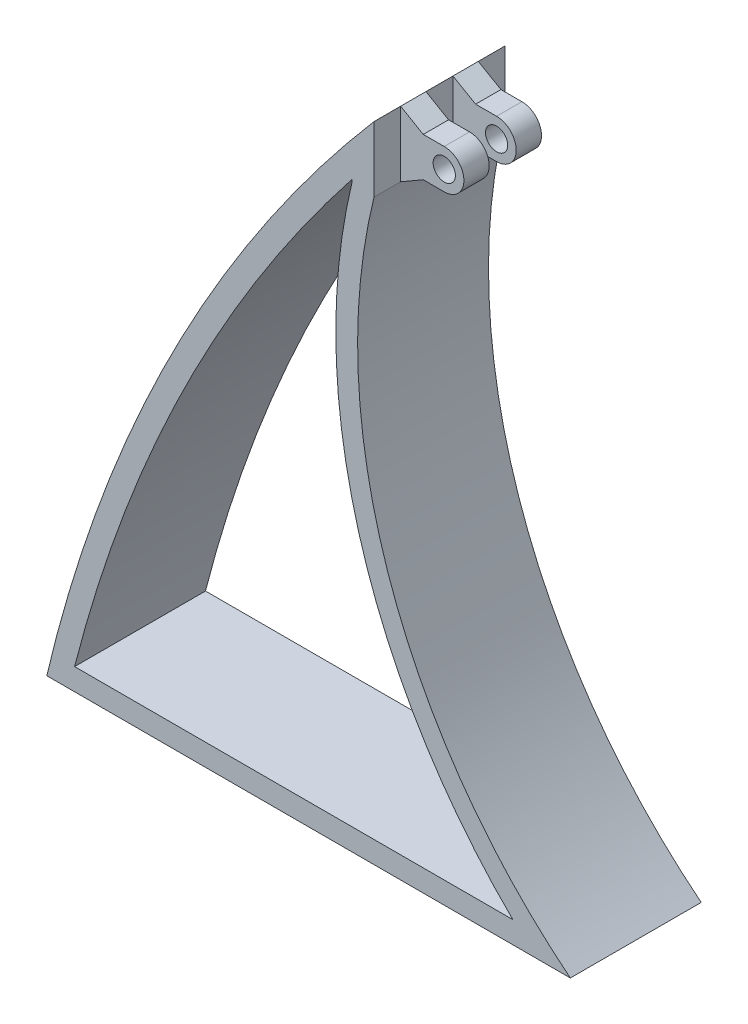
SolidWorks part; units mm, degrees
ref_plane "Front Plane" through (0, 0, 0) normal (0, 0, 1) x (1, 0, 0)
ref_plane "Top Plane" through (0, 0, 0) normal (0, 1, 0) x (1, 0, 0)
ref_plane "Right Plane" through (0, 0, 0) normal (1, 0, 0) x (0, 0, -1)
sketch "Sketch1" plane through (0, 0, 0) normal (0, 0, 1) x (1, 0, 0)
  line L0 (-60, 0) -> (60, 0)
  line L2 (15, 147.5) -> (15, 132.5)
  arc A2 (15, 147.5) -> (-60, 0) centre (280.6426, -80.3903) ccw
  arc A3 (15, 132.5) -> (60, 0) centre (141.2459, 101.4845) ccw
  point P8 (15, 140)
  dimension "D1" = 15
  dimension "D4" = 120
  dimension "D5" = 350
  dimension "D6" = 130
  dimension "D2" = 45
  dimension "D3" = 140
extrude "Boss-Extrude1" add sketch "Sketch1" along normal mid plane 30
sketch "Sketch3" plane through (0, 0, 15) normal (0, 0, 1) x (1, 0, 0)
  line L4 (10, 133.0994) -> (10, 133.5666)
  line L5 (-53.623, 5) -> (46.8227, 5)
  line L6 (10, 133.0994) -> (10, 133.5666)
  line L7 (-53.623, 5) -> (46.8227, 5)
  arc A4 (10, 133.5666) -> (-53.623, 5) centre (280.6426, -80.3903) ccw
  arc A5 (10, 133.0994) -> (46.8227, 5) centre (141.2459, 101.4845) ccw
  arc A6 (10, 133.5666) -> (-53.623, 5) centre (280.6426, -80.3903) ccw
  arc A7 (10, 133.0994) -> (46.8227, 5) centre (141.2459, 101.4845) ccw
  dimension "D1" = 5
extrude "Cut-Extrude1" cut sketch "Sketch3" against normal through all
sketch "Sketch4" plane through (0, 0, 0) normal (0, 0, 1) x (1, 0, 0)
  line L0 (25, 135.5) -> (20.1962, 135.5)
  line L2 (15, 147.5) -> (15, 132.5)
  line L7 (20.1962, 135.5) -> (15, 132.5)
  line L8 (25, 140) -> (40.3949, 140) construction
  line L9 (20.1962, 144.5) -> (15, 147.5)
  line L10 (25, 144.5) -> (20.1962, 144.5)
  circle A0 centre (25, 140) radius 2.55
  arc A1 (25, 144.5) -> (25, 135.5) centre (25, 140) cw
  point P7 (15, 140)
  dimension "D1" = 5.1
  dimension "D3" = 4.5
  dimension "D2" = 10
  dimension "D4" = 60
extrude "Boss-Extrude2" add sketch "Sketch4" along normal blind 5.8 from offset 3.1
mirror "Mirror1" about plane through (0, 0, 0) normal (0, 0, 1) of "Boss-Extrude2"
